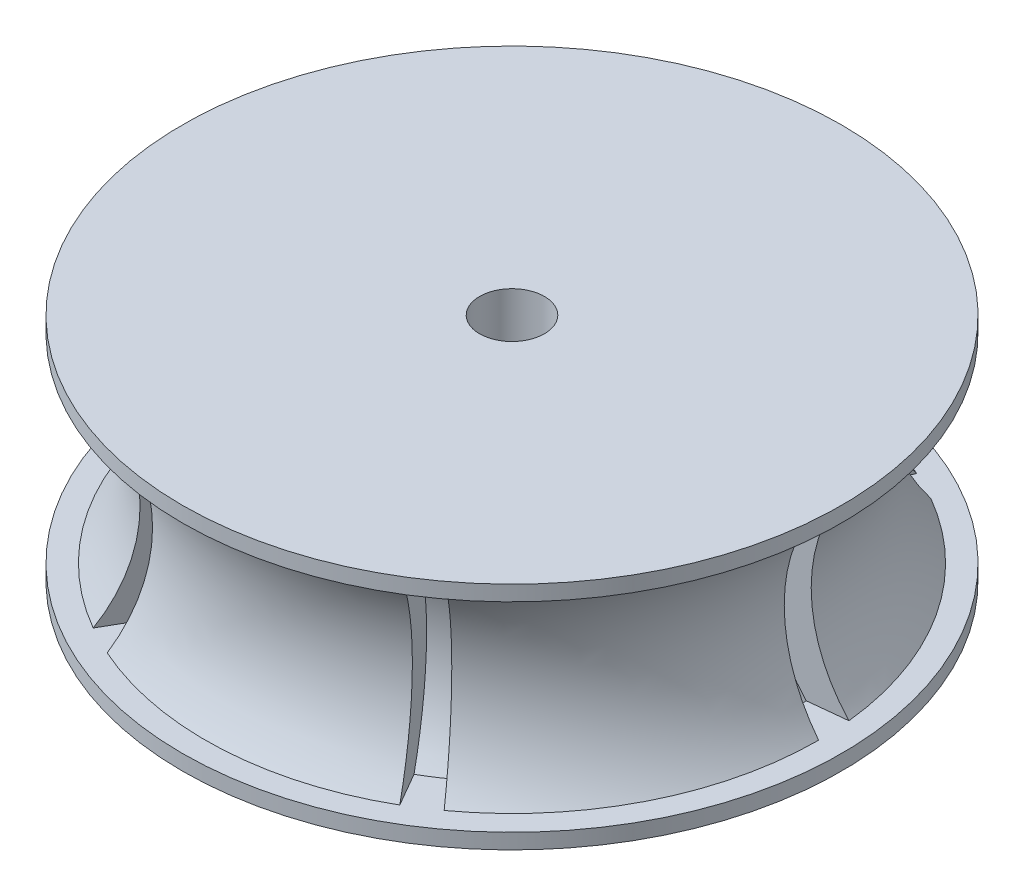
SolidWorks part; units mm, degrees
ref_plane "Front Plane" through (0, 0, 0) normal (0, 0, 1) x (1, 0, 0)
ref_plane "Top Plane" through (0, 0, 0) normal (0, 1, 0) x (1, 0, 0)
ref_plane "Right Plane" through (0, 0, 0) normal (1, 0, 0) x (0, 0, -1)
sketch "Sketch1" plane through (0, 0, 0) normal (1, 0, 0) x (0, 0, -1)
  line L0 (0, 0) -> (-53.34, 0) construction
  line L1 (-60.0728, 19.55) -> (-64.5728, 19.55)
  line L2 (-64.5728, 19.55) -> (-64.5728, 22.55)
  line L3 (-64.5728, 22.55) -> (0, 22.55)
  line L4 (0, 22.55) -> (0, -22.55)
  line L5 (0, -22.55) -> (-64.5728, -22.55)
  line L6 (-64.5728, -22.55) -> (-64.5728, -19.55)
  line L7 (-64.5728, -19.55) -> (-60.0728, -19.55)
  arc A0 (-60.0728, 19.55) -> (-60.0728, -19.55) centre (-85.09, 0) cw
  point P11 (0, 0)
  dimension "D1" = 53.34
  dimension "D2" = 31.75
  dimension "D3" = 39.1
  dimension "D4" = 3
  dimension "D5" = 4.5
revolve "Revolve1" add sketch "Sketch1" angle 360 about L4
sketch "Sketch3" plane through (0, 22.55, 0) normal (0, 1, 0) x (1, 0, 0)
  circle A0 centre (0, 0) radius 6.35
extrude "Cut-Extrude1" cut sketch "Sketch3" against normal through all contours A0
sketch "Sketch4" plane through (0, 0, 0) normal (0, 0, 1) x (1, 0, 0)
  line L0 (-60.0728, 19.55) -> (-52.4528, 19.55)
  line L1 (-60.0728, -19.55) -> (-52.4528, -19.55)
  line L2 (0, 0) -> (-45.72, 0) construction
  line L3 (0, 0) -> (0, 38.543) construction
  line L4 (-60.0728, 19.55) -> (60.0728, 19.55) construction
  arc A0 (-60.0728, -19.55) -> (-60.0728, 19.55) centre (-85.09, 0) ccw construction
  arc A1 (-60.0728, -19.55) -> (-60.0728, 19.55) centre (-85.09, 0) ccw
  arc A2 (-52.4528, 19.55) -> (-52.4528, -19.55) centre (-77.47, 0) cw
  point P4 (-49.8275, 19.05)
  point P13 (-53.34, -19.05)
  point P14 (0, 0)
  dimension "D2" = 31.75
  dimension "D1" = 45.72
revolve "Cut-Revolve5" cut sketch "Sketch4" angle 6 about L3
pattern_circular "CirPattern1" count 6 over 360 about axis through (0, 0, 0) along (0, 1, 0) of "Cut-Revolve5"
